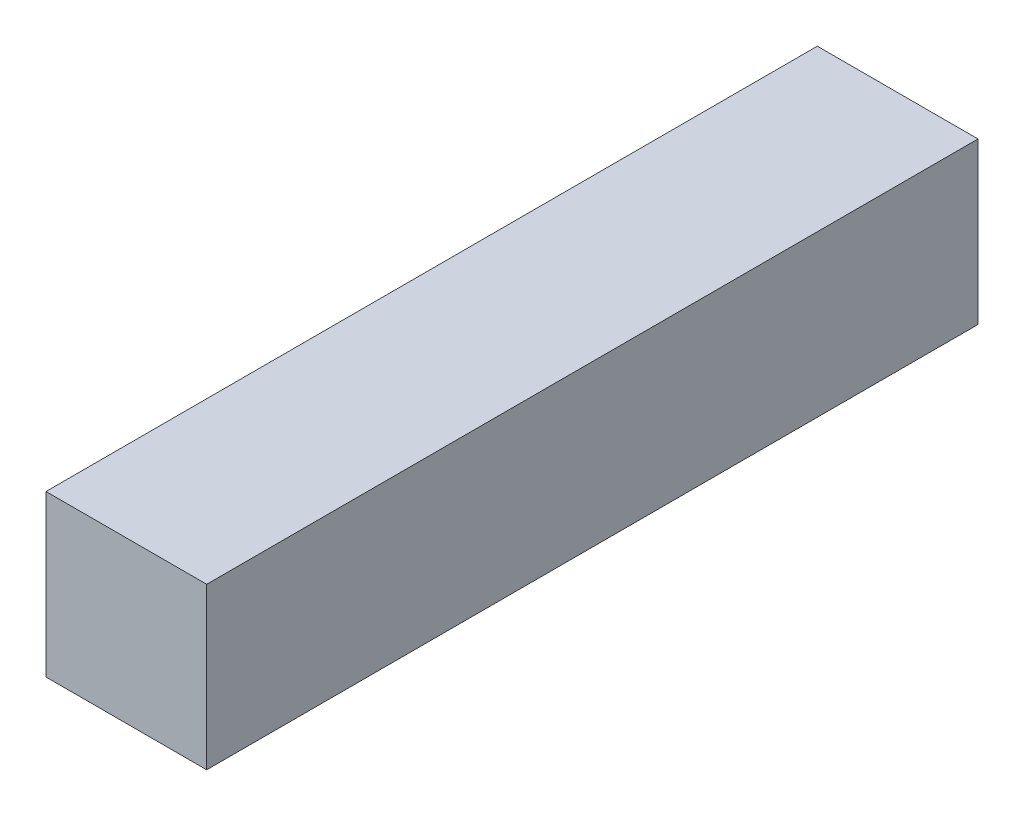
SolidWorks part; units mm, degrees
ref_plane "Front Plane" through (0, 0, 0) normal (0, 0, 1) x (1, 0, 0)
ref_plane "Top Plane" through (0, 0, 0) normal (0, 1, 0) x (1, 0, 0)
ref_plane "Right Plane" through (0, 0, 0) normal (1, 0, 0) x (0, 0, -1)
sketch "Sketch1" plane through (0, 0, 0) normal (0, 0, 1) x (1, 0, 0)
  line L1 (-5, 5) -> (5, 5)
  line L2 (-5, 5) -> (-5, -5)
  line L3 (-5, -5) -> (5, -5)
  line L4 (5, 5) -> (5, -5)
  line L5 (-5, 5) -> (5, -5) construction
  line L6 (-5, -5) -> (5, 5) construction
  point P0 (0, 0)
  dimension "D1" = 10
  dimension "D2" = 10
extrude "Boss-Extrude1" add sketch "Sketch1" along normal mid plane 48
